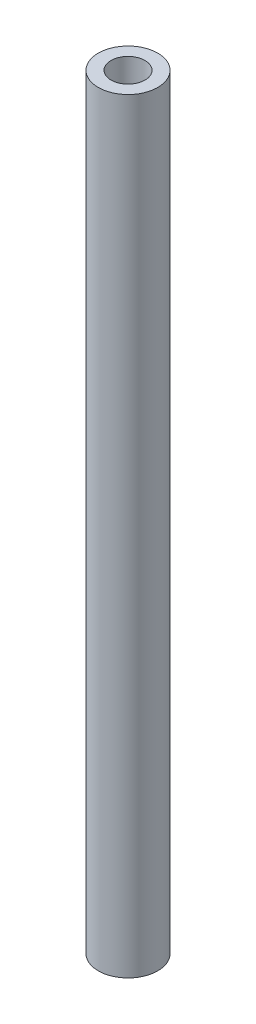
SolidWorks part; units mm, degrees
ref_plane "前视基准面" through (0, 0, 0) normal (0, 0, 1) x (1, 0, 0)
ref_plane "上视基准面" through (0, 0, 0) normal (0, 1, 0) x (1, 0, 0)
ref_plane "右视基准面" through (0, 0, 0) normal (1, 0, 0) x (0, 0, -1)
other "Configuration Table"
sketch "草图1" plane through (0, 0, 0) normal (0, 1, 0) x (1, 0, 0)
  circle A0 centre (0, 0) radius 1.75
  circle A1 centre (0, 0) radius 1
  dimension "D1" = 3.5
  dimension "D2" = 2
extrude "凸台-拉伸1" add sketch "草图1" along normal blind 45
